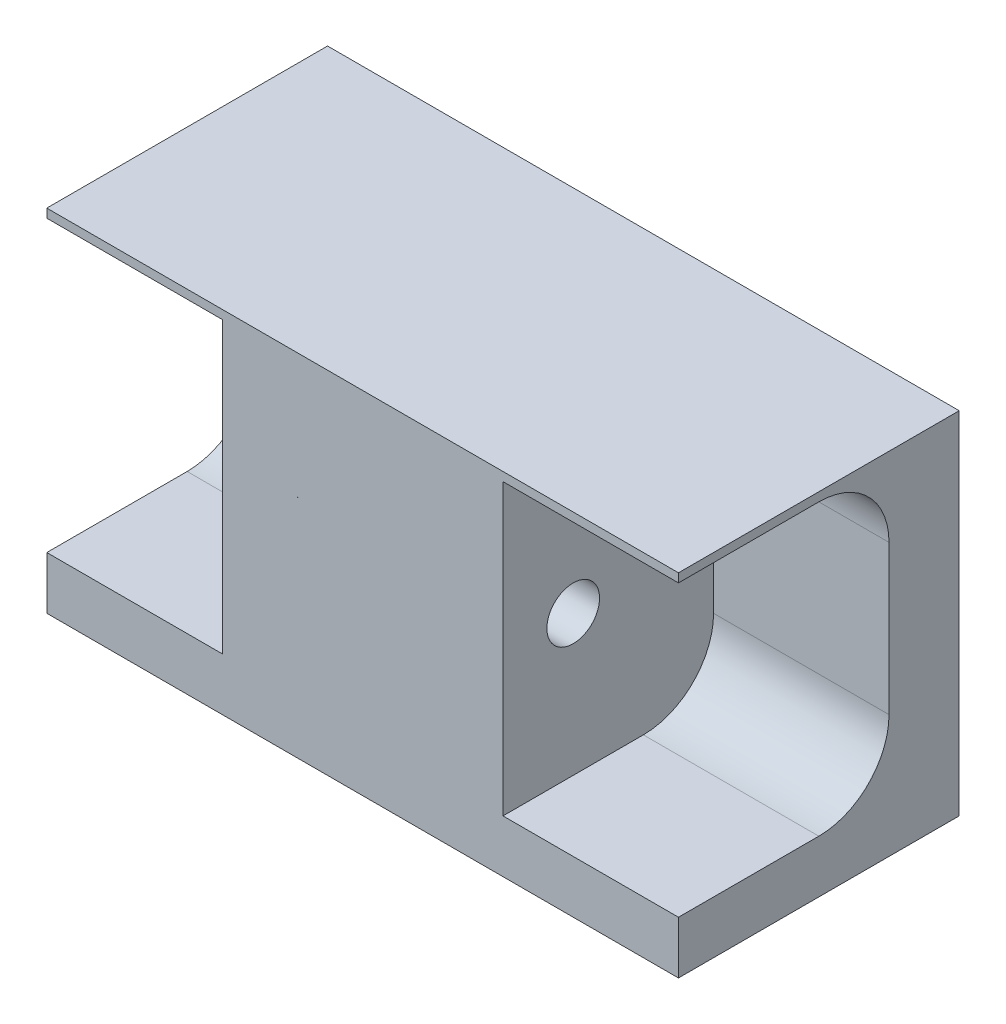
SolidWorks part; units mm, degrees
ref_plane "Front Plane" through (0, 0, 0) normal (0, 0, 1) x (1, 0, 0)
ref_plane "Top Plane" through (0, 0, 0) normal (0, 1, 0) x (1, 0, 0)
ref_plane "Right Plane" through (0, 0, 0) normal (1, 0, 0) x (0, 0, -1)
sketch "Sketch1" plane through (0, 0, 0) normal (1, 0, 0) x (0, 0, -1)
  line L1 (-101.6, 127) -> (101.6, 127)
  line L2 (-101.6, 127) -> (-101.6, -127)
  line L3 (-101.6, -127) -> (101.6, -127)
  line L4 (101.6, 127) -> (101.6, -127)
  line L5 (-101.6, 127) -> (101.6, -127) construction
  line L6 (-101.6, -127) -> (101.6, 127) construction
  point P0 (0, 0)
  dimension "D1" = 203.2
  dimension "D2" = 254
extrude "Boss-Extrude1" add sketch "Sketch1" along normal mid plane 228.6
sketch "Sketch2" plane through (114.3, 0, 0) normal (1, 0, 0) x (0, 0, -1)
  line L0 (-101.6, 120.65) -> (0, 120.65)
  line L1 (-101.6, 127) -> (-101.6, -127) construction
  line L2 (50.8, 69.85) -> (50.8, -38.1)
  line L3 (0, -88.9) -> (-101.6, -88.9)
  line L4 (101.6, 127) -> (-101.6, 127) construction
  line L5 (-101.6, -127) -> (101.6, -127) construction
  line L6 (-101.6, 120.65) -> (-101.6, -88.9)
  arc A0 (50.8, -38.1) -> (0, -88.9) centre (0, -38.1) cw
  arc A1 (0, 120.65) -> (50.8, 69.85) centre (0, 69.85) cw
  dimension "D4" = 50.8
  dimension "D1" = 6.35
  dimension "D2" = 38.1
  dimension "D3" = 152.4
extrude "Cut-Extrude2" cut sketch "Sketch2" against normal blind 127
mirror "Mirror1" about plane through (-114.3, 0, 0) normal (1, 0, 0) of bodies 103
sketch "Sketch3" plane through (0, 0, 0) normal (1, 0, 0) x (0, 0, -1)
  line L0 (-101.6, -88.9) -> (0, -88.9) construction
  line L1 (-101.6, 120.65) -> (-101.6, -88.9) construction
  circle A0 centre (-50.8, 12.7) radius 19.05
  dimension "D1" = 38.1
  dimension "D2" = 101.6
  dimension "D3" = 50.8
extrude "Cut-Extrude3" cut sketch "Sketch3" against normal through all
